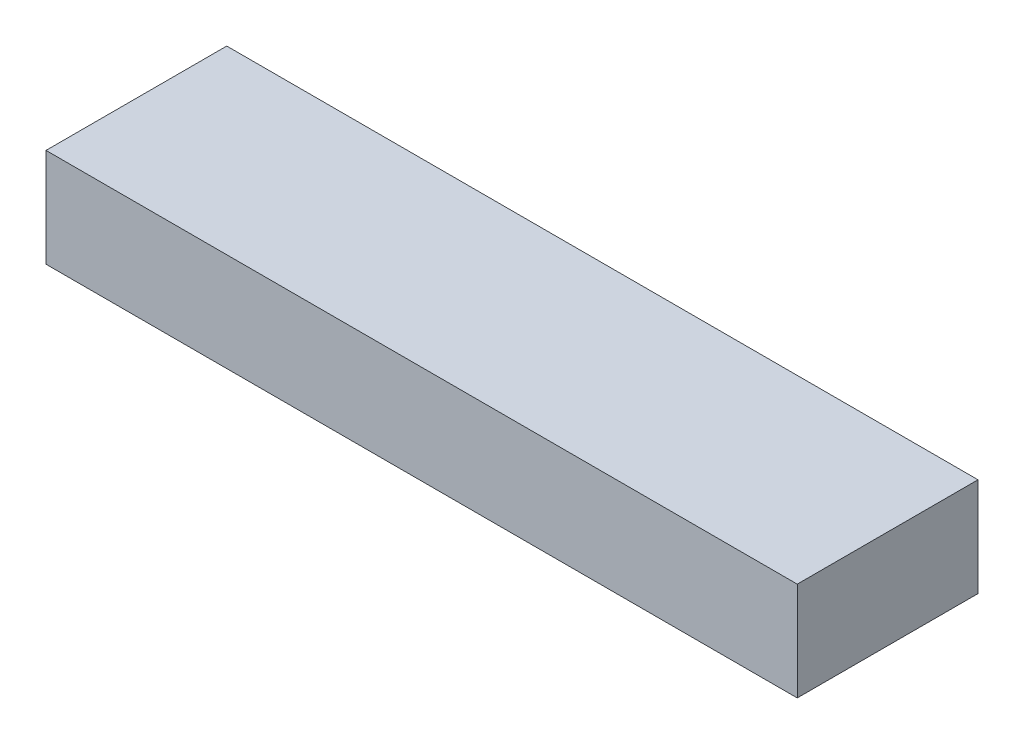
SolidWorks part; units mm, degrees
ref_plane "Front Plane" through (0, 0, 0) normal (0, 0, 1) x (1, 0, 0)
ref_plane "Top Plane" through (0, 0, 0) normal (0, 1, 0) x (1, 0, 0)
ref_plane "Right Plane" through (0, 0, 0) normal (1, 0, 0) x (0, 0, -1)
sketch "Sketch1" plane through (0, 0, 0) normal (0, 1, 0) x (1, 0, 0)
  line L1 (114.3, -27.5) -> (-114.3, -27.5)
  line L2 (114.3, -27.5) -> (114.3, 27.5)
  line L3 (114.3, 27.5) -> (-114.3, 27.5)
  line L4 (-114.3, -27.5) -> (-114.3, 27.5)
  line L5 (114.3, -27.5) -> (-114.3, 27.5) construction
  line L6 (114.3, 27.5) -> (-114.3, -27.5) construction
  point P0 (0, 0)
  dimension "D1" = 55
  dimension "D2" = 228.6
extrude "Boss-Extrude1" add sketch "Sketch1" along normal blind 30
sketch "wood" plane through (0, 30, 0) normal (0, 1, 0) x (1, 0, 0)
  line L0 (-114.3, 27.5) -> (-116.2, 27.5) construction
  dimension "wood_width" = 1.9
equation "\"wood_width\"= 1.9mm"
equation "\"wood_width@wood\"=\"wood_width\""
